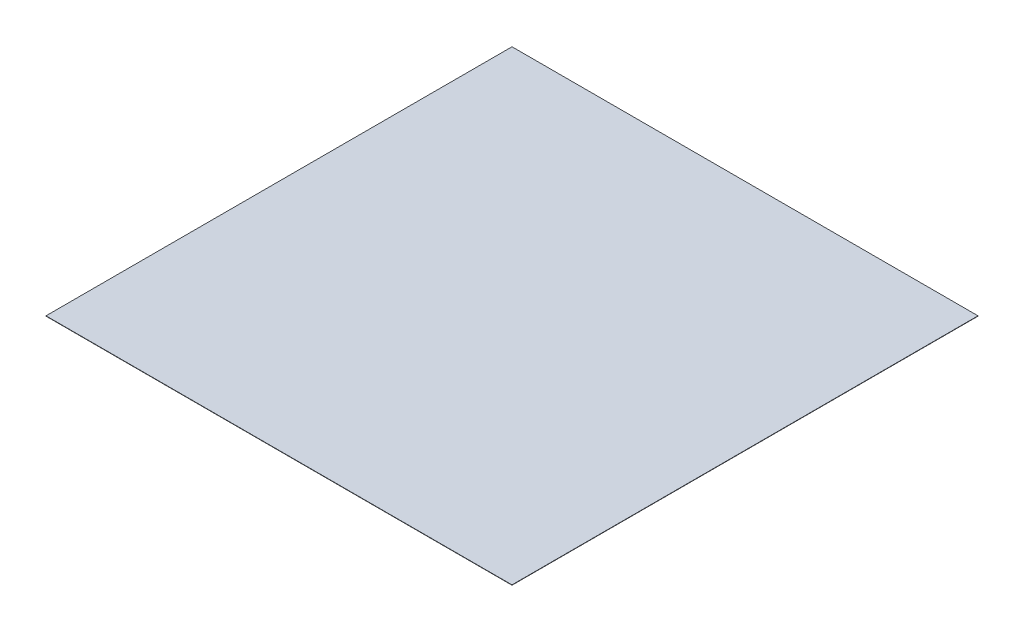
SolidWorks part; units mm, degrees
ref_plane "Front Plane" through (0, 0, 0) normal (0, 0, 1) x (1, 0, 0)
ref_plane "Top Plane" through (0, 0, 0) normal (0, 1, 0) x (1, 0, 0)
ref_plane "Right Plane" through (0, 0, 0) normal (1, 0, 0) x (0, 0, -1)
sketch "Sketch1" plane through (0, 0, 0) normal (0, 1, 0) x (1, 0, 0)
  line L1 (0, 0) -> (14000, 0)
  line L2 (0, 0) -> (0, 14000)
  line L3 (0, 14000) -> (14000, 14000)
  line L4 (14000, 0) -> (14000, 14000)
  dimension "D1" = 14000
  dimension "D2" = 14000
extrude "Boss-Extrude1" add sketch "Sketch1" along normal blind 10
